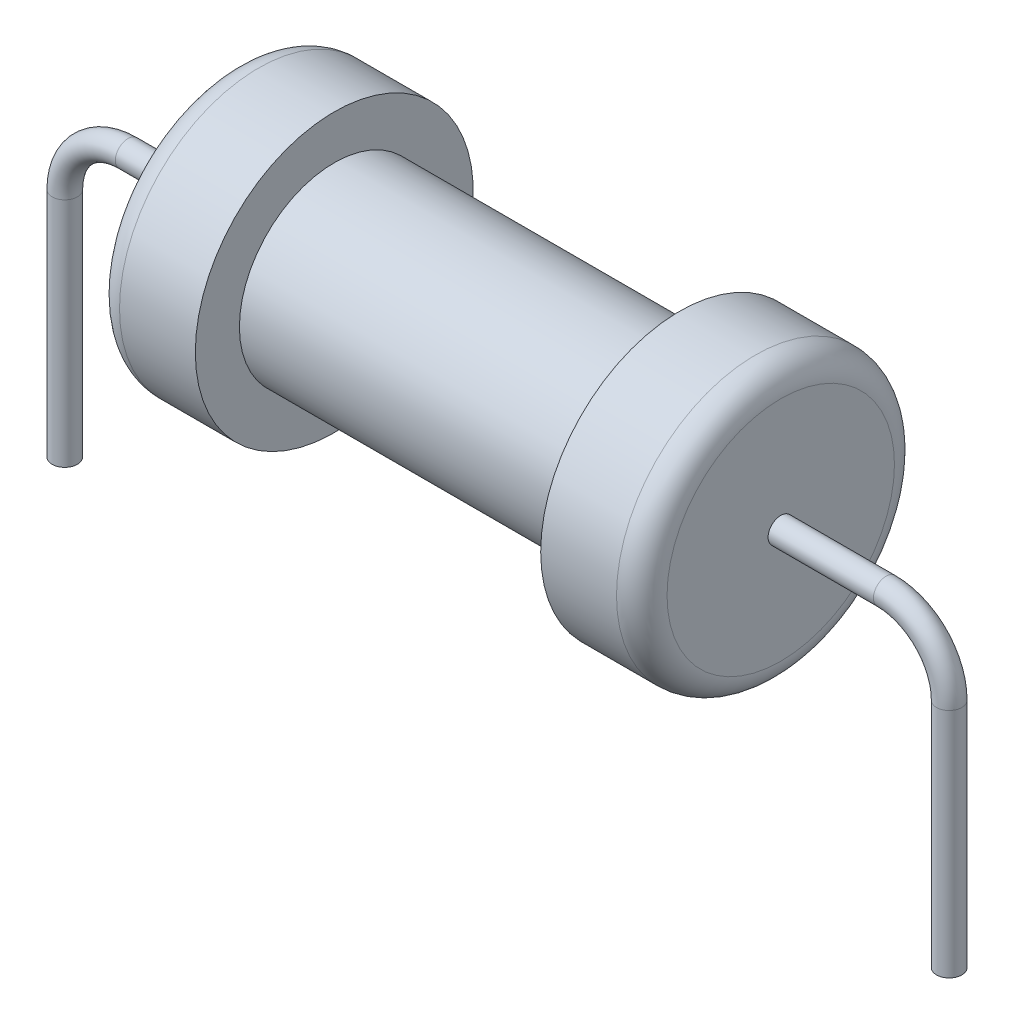
SolidWorks part; units mm, degrees
ref_plane "Front Plane" through (0, 0, 0) normal (0, 0, 1) x (1, 0, 0)
ref_plane "Top Plane" through (0, 0, 0) normal (0, 1, 0) x (1, 0, 0)
ref_plane "Right Plane" through (0, 0, 0) normal (1, 0, 0) x (0, 0, -1)
sketch "Sketch1" plane through (0, 0, 0) normal (0, 1, 0) x (1, 0, 0)
  line L1 (-6500, 2700) -> (-6500, -2700)
  line L2 (4100, -2279.1909) -> (-4100, -2279.1909)
  line L4 (6500, -2700) -> (6500, 2700)
  line L5 (-5900, 3300) -> (-4100, 3300)
  line L6 (-4100, 3300) -> (-4100, -3300)
  line L7 (5900, 3300) -> (4100, 3300)
  line L8 (4100, 3300) -> (4100, -3300)
  line L9 (4100, 2253.2853) -> (-4100, 2253.2853)
  line L10 (-12281.1185, 0) -> (12278.8815, 0) construction
  line L11 (5900, -3300) -> (4100, -3300)
  line L12 (-5900, -3300) -> (-4100, -3300)
  line L13 (-13626.3931, 0) -> (13626.3931, 0) construction
  arc A0 (-6500, 2700) -> (-5900, 3300) centre (-5900, 2700) cw
  arc A1 (-6500, -2700) -> (-5900, -3300) centre (-5900, -2700) ccw
  arc A2 (6500, 2700) -> (5900, 3300) centre (5900, 2700) ccw
  arc A3 (5900, -3300) -> (6500, -2700) centre (5900, -2700) ccw
  point P25 (-4100, 2257.0939)
  point P26 (4100, 2253.2853)
  point P27 (0, 0)
  point P28 (4100, -2279.1909)
  point P29 (0, 0)
  point P30 (-4100, -2279.1909)
  dimension "D1" = 600
  dimension "D2" = 600
  dimension "D3" = 600
  dimension "D4" = 600
sketch "Sketch3" plane through (0, 0, 0) normal (0, 0, 1) x (1, 0, 0)
  line L0 (-6499.254, 0) -> (-8999.254, 0)
  line L1 (-10499.254, -1500) -> (-10499.254, -7000)
  arc A0 (-10499.254, -1500) -> (-8999.254, 0) centre (-8999.254, -1500) cw
  dimension "D1" = 1500
sketch "Sketch4" plane through (0, 0, 0) normal (0, 0, 1) x (1, 0, 0)
  line L0 (10500, -7000) -> (10500, -1500)
  line L1 (9000, 0) -> (6500, 0)
  arc A0 (9000, 0) -> (10500, -1500) centre (9000, -1500) cw
  dimension "D1" = 1500
sweep "Sweep1" add path "Sketch4" circular profile diameter 600 parameters "D3"=600
sweep "Sweep2" add path "Sketch3" circular profile diameter 600 parameters "D3"=600
revolve "Revolve2" add sketch "Sketch1" angle 360 about L10
